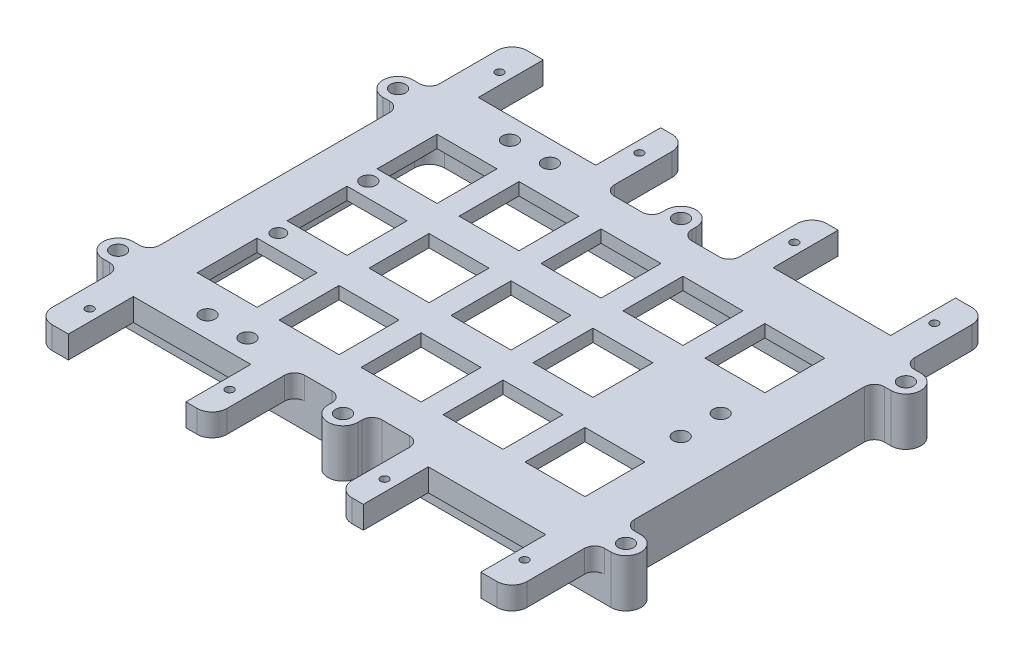
SolidWorks part; units mm, degrees
ref_plane "前视基准面" through (0, 0, 0) normal (0, 0, 1) x (1, 0, 0)
ref_plane "上视基准面" through (0, 0, 0) normal (0, 1, 0) x (1, 0, 0)
ref_plane "右视基准面" through (0, 0, 0) normal (1, 0, 0) x (0, 0, -1)
other "Configuration Table"
sketch "草图1" plane through (0, 0, 0) normal (0, 1, 0) x (1, 0, 0)
  line L0 (0, 35.4779) -> (0, -35.3561) construction
  line L2 (-47.5, 23) -> (-47.5, -23)
  line L4 (47.5, 23) -> (47.5, -23)
  line L5 (-47.5, 31) -> (47.5, -31) construction
  line L6 (-47.5, -31) -> (47.5, 31) construction
  line L15 (-78.7463, 0) -> (58.6748, 0) construction
  line L24 (-10.5, 31) -> (-5, 31)
  line L27 (-10.5, -31) -> (-5, -31)
  line L28 (49.5, 31) -> (50.8, 31)
  line L29 (-49.5, 31) -> (-50.8, 31)
  line L31 (-49.5, 25) -> (-50.8, 25)
  line L33 (49.5, 25) -> (50.8, 25)
  line L36 (49.5, -25) -> (50.8, -25)
  line L37 (49.5, -31) -> (50.8, -31)
  line L38 (-49.5, -31) -> (-50.8, -31)
  line L39 (-49.5, -25) -> (-50.8, -25)
  line L41 (-3, -33.8) -> (-3, -33)
  line L43 (-3, 33.8) -> (-3, 33)
  line L45 (3, 33.8) -> (3, 33)
  line L47 (3, -33.8) -> (3, -33)
  line L48 (5, 31) -> (10.5, 31)
  line L49 (5, -31) -> (10.5, -31)
  line L54 (29.5, 63.8424) -> (29.5, 47.5) construction
  line L56 (47.5, 33) -> (47.5, 44.5)
  line L57 (44.5, 47.5) -> (41.25, 47.5)
  line L58 (12.5, 33) -> (12.5, 44.5)
  line L59 (17.75, 47.5) -> (15.5, 47.5)
  line L60 (17.75, 34.5) -> (41.25, 34.5)
  line L61 (17.75, 34.5) -> (17.75, 47.5)
  line L63 (41.25, 34.5) -> (41.25, 47.5)
  line L65 (12.5, -33) -> (12.5, -44.5)
  line L66 (29.5, 34.5) -> (29.5, 25) construction
  line L67 (17.75, -47.5) -> (15.5, -47.5)
  line L68 (17.75, -34.5) -> (17.75, -47.5)
  line L69 (17.75, -34.5) -> (41.25, -34.5)
  line L70 (41.25, -34.5) -> (41.25, -47.5)
  line L71 (44.5, -47.5) -> (41.25, -47.5)
  line L72 (47.5, -33) -> (47.5, -44.5)
  line L73 (-47.5, -33) -> (-47.5, -44.5)
  line L74 (-44.5, -47.5) -> (-41.25, -47.5)
  line L75 (-41.25, -34.5) -> (-41.25, -47.5)
  line L76 (-17.75, -34.5) -> (-41.25, -34.5)
  line L77 (-17.75, -34.5) -> (-17.75, -47.5)
  line L78 (-17.75, -47.5) -> (-15.5, -47.5)
  line L79 (-12.5, -33) -> (-12.5, -44.5)
  line L82 (-12.5, 33) -> (-12.5, 44.5)
  line L83 (-17.75, 47.5) -> (-15.5, 47.5)
  line L84 (-17.75, 34.5) -> (-17.75, 47.5)
  line L85 (-17.75, 34.5) -> (-41.25, 34.5)
  line L86 (-41.25, 34.5) -> (-41.25, 47.5)
  line L87 (-44.5, 47.5) -> (-41.25, 47.5)
  line L88 (-47.5, 33) -> (-47.5, 44.5)
  arc A4 (-50.8, 31) -> (-50.8, 25) centre (-50.8, 28) ccw
  circle A5 centre (-50.8, 28) radius 1.5
  circle A6 centre (50.8, 28) radius 1.5
  arc A7 (50.8, 31) -> (50.8, 25) centre (50.8, 28) cw
  circle A8 centre (50.8, -28) radius 1.5
  arc A9 (50.8, -31) -> (50.8, -25) centre (50.8, -28) ccw
  circle A10 centre (-50.8, -28) radius 1.5
  arc A11 (-50.8, -31) -> (-50.8, -25) centre (-50.8, -28) cw
  arc A12 (-3, 33.8) -> (3, 33.8) centre (0, 33.8) cw
  circle A13 centre (0, 33.8) radius 1.5
  circle A14 centre (0, -33.8) radius 1.5
  arc A15 (-3, -33.8) -> (3, -33.8) centre (0, -33.8) ccw
  arc A16 (47.5, 44.5) -> (44.5, 47.5) centre (44.5, 44.5) ccw
  arc A17 (15.5, 47.5) -> (12.5, 44.5) centre (15.5, 44.5) ccw
  circle A18 centre (43.5, 41) radius 0.8
  circle A19 centre (15.5, 41) radius 0.8
  circle A20 centre (43.5, -41) radius 0.8
  circle A21 centre (15.5, -41) radius 0.8
  arc A22 (15.5, -47.5) -> (12.5, -44.5) centre (15.5, -44.5) cw
  arc A23 (47.5, -44.5) -> (44.5, -47.5) centre (44.5, -44.5) cw
  circle A24 centre (-15.5, -41) radius 0.8
  circle A25 centre (-43.5, -41) radius 0.8
  arc A26 (-47.5, -44.5) -> (-44.5, -47.5) centre (-44.5, -44.5) ccw
  arc A27 (-15.5, -47.5) -> (-12.5, -44.5) centre (-15.5, -44.5) ccw
  circle A28 centre (-43.5, 41) radius 0.8
  circle A29 centre (-15.5, 41) radius 0.8
  arc A30 (-15.5, 47.5) -> (-12.5, 44.5) centre (-15.5, 44.5) cw
  arc A31 (-47.5, 44.5) -> (-44.5, 47.5) centre (-44.5, 44.5) cw
  arc A32 (47.5, -23) -> (49.5, -25) centre (49.5, -23) ccw
  arc A33 (49.5, 25) -> (47.5, 23) centre (49.5, 23) ccw
  arc A34 (-49.5, -25) -> (-47.5, -23) centre (-49.5, -23) ccw
  arc A35 (-47.5, 23) -> (-49.5, 25) centre (-49.5, 23) ccw
  arc A36 (-49.5, -31) -> (-47.5, -33) centre (-49.5, -33) cw
  arc A37 (-12.5, -33) -> (-10.5, -31) centre (-10.5, -33) cw
  arc A38 (-3, -33) -> (-5, -31) centre (-5, -33) ccw
  arc A39 (5, -31) -> (3, -33) centre (5, -33) ccw
  arc A40 (10.5, -31) -> (12.5, -33) centre (10.5, -33) cw
  arc A41 (47.5, -33) -> (49.5, -31) centre (49.5, -33) cw
  arc A42 (47.5, 33) -> (49.5, 31) centre (49.5, 33) ccw
  arc A43 (10.5, 31) -> (12.5, 33) centre (10.5, 33) ccw
  arc A44 (5, 31) -> (3, 33) centre (5, 33) cw
  arc A45 (-3, 33) -> (-5, 31) centre (-5, 33) cw
  arc A46 (-10.5, 31) -> (-12.5, 33) centre (-10.5, 33) cw
  arc A47 (-47.5, 33) -> (-49.5, 31) centre (-49.5, 33) cw
  point P0 (0, 0)
  point P14 (47.5, -25)
  point P21 (29.5, 41)
  point P24 (47.5, 25)
  point P62 (47.5, 47.5)
  point P65 (12.5, 47.5)
  point P117 (-47.5, -25)
  point P120 (-47.5, 25)
  point P126 (-12.5, -31)
  point P129 (-3, -31)
  point P132 (3, -31)
  point P135 (12.5, -31)
  point P144 (12.5, 31)
  point P147 (3, 31)
  point P150 (-3, 31)
  point P153 (-12.5, 31)
  dimension "D8" = 2.8
  dimension "D11" = 3
  dimension "D12" = 6.5
  dimension "D3" = 2
  dimension "D1" = 95
  dimension "D2" = 62
  dimension "D4" = 35
  dimension "D5" = 23.5
  dimension "D6" = 3.3
  dimension "D7" = 6
  dimension "D9" = 6
  dimension "D13" = 2.25
extrude "凸台-拉伸1" add sketch "草图1" against normal blind 9.6
sketch "草图2" plane through (0, -9.6, 0) normal (0, -1, 0) x (1, 0, 0)
  line L0 (-63.1336, 0) -> (63.5579, 0) construction
  line L5 (0, 56.9992) -> (0, 48.5806) construction
  line L18 (3, 33.8) -> (3, 33) construction
  line L19 (63.5579, 31) -> (5, 31)
  line L20 (63.5579, 31) -> (63.5579, 53.6942)
  line L21 (63.5579, 53.6942) -> (-73.0103, 53.6942)
  line L22 (-73.0103, 31) -> (-73.0103, 53.6942)
  line L23 (-3, 33) -> (-3, 33.8) construction
  line L24 (3, 33.8) -> (3, 33)
  line L25 (-3, 33) -> (-3, 33.8)
  line L26 (-5, 31) -> (-73.0103, 31)
  line L27 (63.5579, -31) -> (63.5579, -53.6942)
  line L28 (63.5579, -53.6942) -> (-73.0103, -53.6942)
  line L29 (-73.0103, -31) -> (-73.0103, -53.6942)
  line L30 (-5, -31) -> (-73.0103, -31)
  line L31 (-3, -33) -> (-3, -33.8)
  line L32 (3, -33.8) -> (3, -33)
  line L33 (63.5579, -31) -> (5, -31)
  arc A3 (3, 33) -> (5, 31) centre (5, 33) ccw construction
  arc A4 (3, 33.8) -> (-3, 33.8) centre (0, 33.8) ccw construction
  arc A5 (-5, 31) -> (-3, 33) centre (-5, 33) ccw construction
  arc A6 (3, 33) -> (5, 31) centre (5, 33) ccw
  arc A7 (3, 33.8) -> (-3, 33.8) centre (0, 33.8) ccw
  arc A8 (-5, 31) -> (-3, 33) centre (-5, 33) ccw
  arc A9 (-5, -31) -> (-3, -33) centre (-5, -33) cw
  arc A10 (3, -33.8) -> (-3, -33.8) centre (0, -33.8) cw
  arc A11 (3, -33) -> (5, -31) centre (5, -33) cw
extrude "切除-拉伸1" cut sketch "草图2" against normal blind 5.1
sketch "草图3" plane through (0, -9.6, 0) normal (0, -1, 0) x (1, 0, 0)
  line L0 (47.5, 23) -> (47.5, -23) construction
  line L1 (-45, -28.5) -> (45, -28.5)
  line L2 (-45, -28.5) -> (-45, 28.5)
  line L3 (-45, 28.5) -> (45, 28.5)
  line L4 (45, -28.5) -> (45, 28.5)
  line L5 (-45, -28.5) -> (45, 28.5) construction
  line L6 (-45, 28.5) -> (45, -28.5) construction
  line L7 (-50.8, 31) -> (-5, 31) construction
  point P0 (0, 0)
  dimension "D1" = 2.5
  dimension "D2" = 2.5
extrude "切除-拉伸2" cut sketch "草图3" against normal blind 7.1
fillet "圆角1" radius 3 4 edges at (-45, -6.05, -28.5) (-45, -6.05, 28.5) (45, -6.05, -28.5) (45, -6.05, 28.5)
sketch "草图11" plane through (0, -2.5, 0) normal (0, -1, 0) x (1, 0, 0)
  line L0 (0, 44.5522) -> (0, -50.2123) construction
  line L1 (-64.7486, 0) -> (58.5739, 0) construction
  line L2 (42, 28.5) -> (-42, 28.5) construction
  line L3 (-30, 17) -> (30, 17)
  line L4 (-30, 17) -> (-30, 19.5)
  line L5 (-30, 19.5) -> (-1.5, 19.5)
  line L6 (30, 17) -> (30, 19.5)
  line L7 (-30, 17) -> (30, 19.5) construction
  line L8 (-30, 19.5) -> (30, 17) construction
  line L9 (1.5, 19.5) -> (30, 19.5)
  line L10 (-1.5, 28.5) -> (1.5, 28.5)
  line L11 (-1.5, 28.5) -> (-1.5, 19.5)
  line L13 (1.5, 28.5) -> (1.5, 19.5)
  line L14 (1.5, -28.5) -> (1.5, -19.5)
  line L15 (-1.5, -28.5) -> (1.5, -28.5)
  line L16 (-1.5, -28.5) -> (-1.5, -19.5)
  line L17 (-30, -19.5) -> (-1.5, -19.5)
  line L18 (-30, -17) -> (-30, -19.5)
  line L19 (-30, -17) -> (30, -17)
  line L20 (30, -17) -> (30, -19.5)
  line L21 (1.5, -19.5) -> (30, -19.5)
  point P5 (0, 18.25)
  dimension "D1" = 60
  dimension "D2" = 2.5
  dimension "D3" = 9
  dimension "D4" = 3
extrude "凸台-拉伸2" [suppressed] add sketch "草图11" along normal blind 2
sketch "草图12" plane through (0, -2.5, 0) normal (0, -1, 0) x (1, 0, 0)
  line L0 (0, 44.2091) -> (0, -42.6655) construction
  line L1 (-42, 25.5) -> (-7, 25.5)
  line L2 (-42, 25.5) -> (-42, 23)
  line L3 (-42, 23) -> (-7, 23)
  line L4 (-7, 25.5) -> (-7, 23)
  line L5 (-53.0853, 0) -> (71.5236, 0) construction
  line L6 (42, 23) -> (7, 23)
  line L7 (7, 25.5) -> (7, 23)
  line L8 (42, 25.5) -> (7, 25.5)
  line L9 (42, 25.5) -> (42, 23)
  line L10 (42, -25.5) -> (42, -23)
  line L11 (42, -25.5) -> (7, -25.5)
  line L12 (7, -25.5) -> (7, -23)
  line L13 (42, -23) -> (7, -23)
  line L14 (-42, -23) -> (-7, -23)
  line L15 (-7, -25.5) -> (-7, -23)
  line L16 (-42, -25.5) -> (-7, -25.5)
  line L17 (-42, -25.5) -> (-42, -23)
  dimension "D1" = 35
  dimension "D2" = 2.5
fillet "圆角2" radius 1 8 edges at (0, -2.5, -28.5) (-44.1213, -2.5, -27.6213) (-45, -2.5, 0) (-44.1213, -2.5, 27.6213) (0, -2.5, 28.5) (44.1213, -2.5, 27.6213) (45, -2.5, 0) (44.1213, -2.5, -27.6213)
sketch "草图13" plane through (0, -2.5, 0) normal (0, -1, 0) x (1, 0, 0)
  line L0 (-56.0869, 0) -> (61.3182, 0) construction
  line L1 (0, 42.7512) -> (0, -42.4082) construction
  line L2 (-45, -25.5) -> (-45, 25.5) construction
  line L3 (-39, 24) -> (-27, 24)
  line L4 (-39, 24) -> (-39, 12)
  line L5 (-39, 12) -> (-27, 12)
  line L6 (-27, 24) -> (-27, 12)
  line L7 (-39, 24) -> (-27, 12) construction
  line L8 (-39, 12) -> (-27, 24) construction
  line L9 (-22.6, 24) -> (-22.6, 12)
  line L10 (-22.6, 24) -> (-10.6, 24)
  line L11 (-10.6, 24) -> (-10.6, 12)
  line L12 (-22.6, 12) -> (-10.6, 12)
  line L13 (-6.2, 24) -> (-6.2, 12)
  line L14 (-6.2, 24) -> (5.8, 24)
  line L15 (5.8, 24) -> (5.8, 12)
  line L16 (-6.2, 12) -> (5.8, 12)
  line L17 (10.2, 24) -> (10.2, 12)
  line L18 (10.2, 24) -> (22.2, 24)
  line L19 (22.2, 24) -> (22.2, 12)
  line L20 (10.2, 12) -> (22.2, 12)
  line L21 (26.6, 24) -> (26.6, 12)
  line L22 (26.6, 24) -> (38.6, 24)
  line L23 (38.6, 24) -> (38.6, 12)
  line L24 (26.6, 12) -> (38.6, 12)
  line L25 (-22.6, 6) -> (-22.6, -6)
  line L26 (-22.6, 6) -> (-10.6, 6)
  line L27 (-10.6, 6) -> (-10.6, -6)
  line L28 (-22.6, -6) -> (-10.6, -6)
  line L29 (-6.2, 6) -> (-6.2, -6)
  line L30 (-6.2, 6) -> (5.8, 6)
  line L31 (5.8, 6) -> (5.8, -6)
  line L32 (-6.2, -6) -> (5.8, -6)
  line L33 (10.2, 6) -> (10.2, -6)
  line L34 (10.2, 6) -> (22.2, 6)
  line L35 (22.2, 6) -> (22.2, -6)
  line L36 (10.2, -6) -> (22.2, -6)
  line L41 (-22.6, -12) -> (-22.6, -24)
  line L42 (-22.6, -12) -> (-10.6, -12)
  line L43 (-10.6, -12) -> (-10.6, -24)
  line L44 (-22.6, -24) -> (-10.6, -24)
  line L45 (-6.2, -12) -> (-6.2, -24)
  line L46 (-6.2, -12) -> (5.8, -12)
  line L47 (5.8, -12) -> (5.8, -24)
  line L48 (-6.2, -24) -> (5.8, -24)
  line L49 (10.2, -12) -> (10.2, -24)
  line L50 (10.2, -12) -> (22.2, -12)
  line L51 (22.2, -12) -> (22.2, -24)
  line L52 (10.2, -24) -> (22.2, -24)
  line L53 (26.6, -12) -> (26.6, -24)
  line L54 (26.6, -12) -> (38.6, -12)
  line L55 (38.6, -12) -> (38.6, -24)
  line L56 (26.6, -24) -> (38.6, -24)
  line L57 (-39, 6) -> (-39, -6)
  line L58 (-39, 6) -> (-27, 6)
  line L59 (-27, 6) -> (-27, -6)
  line L60 (-39, -6) -> (-27, -6)
  line L61 (-39, -12) -> (-39, -24)
  line L62 (-39, -12) -> (-27, -12)
  line L63 (-27, -12) -> (-27, -24)
  line L64 (-39, -24) -> (-27, -24)
  line L65 (26.6, 6) -> (38.6, 6) [skipped]
  line L66 (38.6, 0) -> (38.6, -6) [skipped]
  line L67 (26.6, -6) -> (38.6, -6) [skipped]
  line L68 (26.6, 0) -> (26.6, -6) [skipped]
  point P5 (-33, 18)
  dimension "D1" = 12
  dimension "D2" = 12
  dimension "D3" = 18
  dimension "D4" = 12
  dimension "D5" = 5
  dimension "D6" = 3
extrude "切除-拉伸3" cut sketch "草图13" against normal through all
sketch "草图14" plane through (0, 0, 0) normal (0, 1, 0) x (1, 0, 0)
  line L0 (-62.6904, 0) -> (58.1451, 0) construction
  line L1 (0, 43.18) -> (0, -40.693) construction
  line L2 (-57.3733, 27.25) -> (53.7714, 27.25) construction
  line L3 (-57.3733, -27.25) -> (53.7714, -27.25) construction
  line L4 (-34.75, 40.8523) -> (-34.75, -44.2213) construction
  line L5 (34.75, 40.8523) -> (34.75, -44.2213) construction
  line L6 (-37.75, 9) -> (-37.75, -9) construction
  line L7 (-34.75, 9) -> (-34.75, -9)
  line L8 (-40.75, 9) -> (-40.75, -9)
  line L9 (37.75, -4) -> (37.75, 4) construction
  line L10 (34.75, -4) -> (34.75, 4)
  line L11 (40.75, -4) -> (40.75, 4)
  line L12 (-30.6682, 30.25) -> (-22.6682, 30.25) construction
  line L13 (-30.6682, 33.25) -> (-22.6682, 33.25)
  line L14 (-30.6682, 27.25) -> (-22.6682, 27.25)
  line L15 (-30.6682, -30.25) -> (-22.6682, -30.25) construction
  line L16 (-30.6682, -33.25) -> (-22.6682, -33.25)
  line L17 (-30.6682, -27.25) -> (-22.6682, -27.25)
  arc A0 (-34.75, 9) -> (-40.75, 9) centre (-37.75, 9) ccw
  arc A1 (-40.75, -9) -> (-34.75, -9) centre (-37.75, -9) ccw
  circle A2 centre (-37.75, 9) radius 1.5
  circle A3 centre (-37.75, -9) radius 1.334
  arc A4 (34.75, -4) -> (40.75, -4) centre (37.75, -4) ccw
  arc A5 (40.75, 4) -> (34.75, 4) centre (37.75, 4) ccw
  circle A6 centre (37.75, 4) radius 1.5
  circle A7 centre (37.75, -4) radius 1.5
  arc A8 (-30.6682, 33.25) -> (-30.6682, 27.25) centre (-30.6682, 30.25) ccw
  arc A9 (-22.6682, 27.25) -> (-22.6682, 33.25) centre (-22.6682, 30.25) ccw
  circle A10 centre (-30.6682, 30.25) radius 1.5
  circle A11 centre (-22.6682, 30.25) radius 1.5
  arc A12 (-30.6682, -33.25) -> (-30.6682, -27.25) centre (-30.6682, -30.25) cw
  arc A13 (-22.6682, -27.25) -> (-22.6682, -33.25) centre (-22.6682, -30.25) cw
  circle A14 centre (-30.6682, -30.25) radius 1.5
  circle A15 centre (-22.6682, -30.25) radius 1.5
  point P15 (-37.75, 0)
  point P25 (37.75, 0)
  point P37 (-26.6682, 30.25)
  point P48 (-26.6682, -30.25)
  dimension "D3" = 3
  dimension "D6" = 3
  dimension "D9" = 3
  dimension "D1" = 54.5
  dimension "D2" = 69.5
  dimension "D4" = 18
  dimension "D5" = 0
  dimension "D7" = 0
  dimension "D8" = 8
  dimension "D10" = 0
  dimension "D11" = 8
extrude "凸台-拉伸4" add sketch "草图14" along normal blind 3 contours L8 A1 L7 A0 A3 A2 | L11 A5 L10 A4 A7 A6 | L14 A9 L13 A8 A11 A10 | A13 L17 A12 L16 A14 A15
sketch "草图16" plane through (0, 0, 0) normal (0, 1, 0) x (1, 0, 0)
  circle A0 centre (37.75, 4) radius 1.5 construction
  circle A1 centre (37.75, -4) radius 1.5 construction
  circle A2 centre (-22.6682, -30.25) radius 1.5 construction
  circle A3 centre (-30.6682, -30.25) radius 1.5 construction
  circle A4 centre (-37.75, -9) radius 1.334 construction
  circle A5 centre (-37.75, 9) radius 1.5 construction
  circle A6 centre (-22.6682, 30.25) radius 1.5 construction
  circle A7 centre (-30.6682, 30.25) radius 1.5 construction
  circle A8 centre (37.75, 4) radius 1.5
  circle A9 centre (37.75, -4) radius 1.5
  circle A10 centre (-22.6682, -30.25) radius 1.5
  circle A11 centre (-30.6682, -30.25) radius 1.5
  circle A12 centre (-37.75, -9) radius 1.334
  circle A13 centre (-37.75, 9) radius 1.5
  circle A14 centre (-22.6682, 30.25) radius 1.5
  circle A15 centre (-30.6682, 30.25) radius 1.5
extrude "切除-拉伸4" cut sketch "草图16" against normal up to surface (4.5 mm away) up to face at (-29.8333, -4.5, 39.7012)
sketch "草图17" plane through (0, 0, 0) normal (0, 1, 0) x (1, 0, 0)
  line L1 (-63.548, 51.6702) -> (63.548, 51.6702)
  line L2 (-63.548, 51.6702) -> (-63.548, -51.6702)
  line L3 (-63.548, -51.6702) -> (63.548, -51.6702)
  line L4 (63.548, 51.6702) -> (63.548, -51.6702)
  line L5 (-63.548, 51.6702) -> (63.548, -51.6702) construction
  line L6 (-63.548, -51.6702) -> (63.548, 51.6702) construction
  point P0 (0, 0)
extrude "切除-拉伸5" cut sketch "草图17" along normal through all
